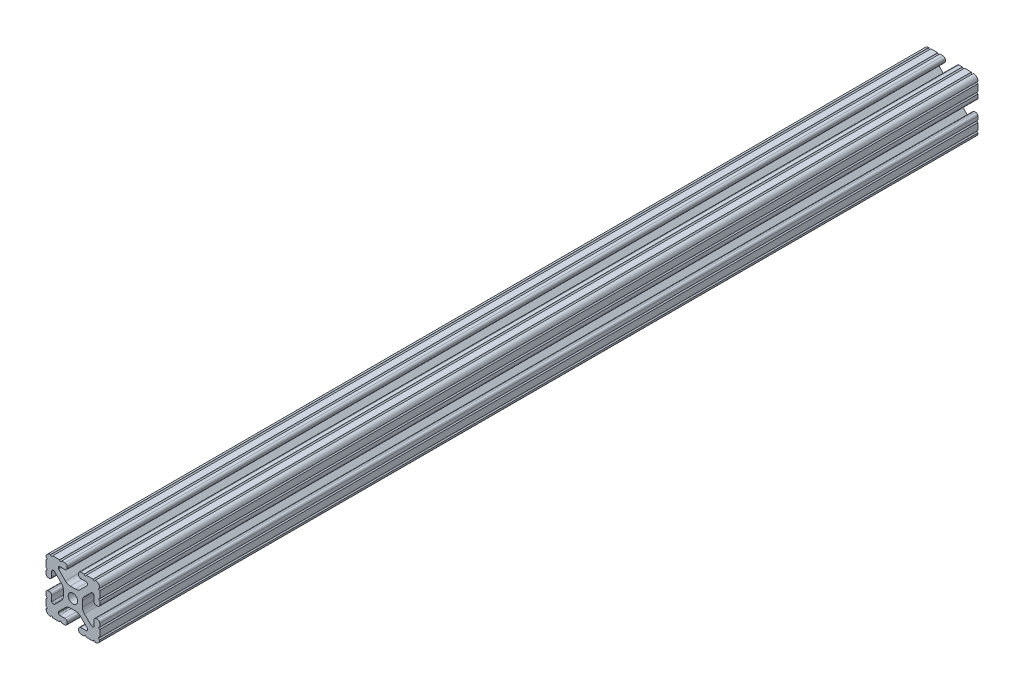
SolidWorks part; units mm, degrees
material "6105-T5 Aluminum"
ref_plane "Front Plane" through (0, 0, 0) normal (0, 0, 1) x (1, 0, 0)
ref_plane "Top Plane" through (0, 0, 0) normal (0, 1, 0) x (1, 0, 0)
ref_plane "Right Plane" through (0, 0, 0) normal (1, 0, 0) x (0, 0, -1)
sketch "Sketch1" plane through (0, 0, 0) normal (0, 0, 1) x (1, 0, 0)
  line L0 (-14.097, 10.287) -> (-13.5289, 10.287)
  line L1 (-12.9003, 10.0266) -> (-8.1292, 5.2555)
  line L2 (-6.738, 1.8969) -> (-6.738, -1.8969)
  line L3 (-8.1292, -5.2555) -> (-12.9003, -10.0266)
  line L4 (-13.5289, -10.287) -> (-14.097, -10.287)
  line L5 (-14.986, -9.398) -> (-14.986, -5.6388)
  line L6 (-16.5608, -4.064) -> (-17.4752, -4.064)
  line L7 (-19.05, -5.6388) -> (-19.05, -7.9756)
  line L8 (-19.05, -9.4996) -> (-19.05, -14.3256)
  line L9 (-19.05, -15.8496) -> (-19.05, -15.875)
  line L10 (-15.875, -19.05) -> (-15.8496, -19.05)
  line L11 (-14.3256, -19.05) -> (-9.4996, -19.05)
  line L12 (-7.9756, -19.05) -> (-5.6388, -19.05)
  line L13 (-4.064, -17.4752) -> (-4.064, -16.5608)
  line L14 (-5.6388, -14.986) -> (-9.398, -14.986)
  line L15 (-10.287, -14.097) -> (-10.287, -13.5289)
  line L16 (-10.0266, -12.9003) -> (-5.2555, -8.1292)
  line L17 (-1.8969, -6.738) -> (1.8969, -6.738)
  line L18 (5.2555, -8.1292) -> (10.0266, -12.9003)
  line L19 (10.287, -13.5289) -> (10.287, -14.097)
  line L20 (9.398, -14.986) -> (5.6388, -14.986)
  line L21 (4.064, -16.5608) -> (4.064, -17.4752)
  line L22 (5.6388, -19.05) -> (7.9756, -19.05)
  line L23 (9.4996, -19.05) -> (14.3256, -19.05)
  line L24 (15.8496, -19.05) -> (15.875, -19.05)
  line L25 (19.05, -15.875) -> (19.05, -15.8496)
  line L26 (19.05, -14.3256) -> (19.05, -9.4996)
  line L27 (19.05, -7.9756) -> (19.05, -5.6388)
  line L28 (17.4752, -4.064) -> (16.5608, -4.064)
  line L29 (14.986, -5.6388) -> (14.986, -9.398)
  line L30 (14.097, -10.287) -> (13.5289, -10.287)
  line L31 (12.9003, -10.0266) -> (8.1292, -5.2555)
  line L32 (6.738, -1.8969) -> (6.738, 1.8969)
  line L33 (8.1292, 5.2555) -> (12.9003, 10.0266)
  line L34 (13.5289, 10.287) -> (14.097, 10.287)
  line L35 (14.986, 9.398) -> (14.986, 5.6388)
  line L36 (16.5608, 4.064) -> (17.4752, 4.064)
  line L37 (19.05, 5.6388) -> (19.05, 7.9756)
  line L38 (19.05, 9.4996) -> (19.05, 14.3256)
  line L39 (19.05, 15.8496) -> (19.05, 15.875)
  line L40 (15.875, 19.05) -> (15.8496, 19.05)
  line L41 (14.3256, 19.05) -> (9.4996, 19.05)
  line L42 (7.9756, 19.05) -> (5.6388, 19.05)
  line L43 (4.064, 17.4752) -> (4.064, 16.5608)
  line L44 (5.6388, 14.986) -> (9.398, 14.986)
  line L45 (10.287, 14.097) -> (10.287, 13.5289)
  line L46 (10.0266, 12.9003) -> (5.2555, 8.1292)
  line L47 (1.8969, 6.738) -> (-1.8969, 6.738)
  line L48 (-5.2555, 8.1292) -> (-10.0266, 12.9003)
  line L49 (-10.287, 13.5289) -> (-10.287, 14.097)
  line L50 (-9.398, 14.986) -> (-5.6388, 14.986)
  line L51 (-4.064, 16.5608) -> (-4.064, 17.4752)
  line L52 (-5.6388, 19.05) -> (-7.9756, 19.05)
  line L53 (-9.4996, 19.05) -> (-14.3256, 19.05)
  line L54 (-15.8496, 19.05) -> (-15.875, 19.05)
  line L55 (-19.05, 15.875) -> (-19.05, 15.8496)
  line L56 (-19.05, 14.3256) -> (-19.05, 9.4996)
  line L57 (-19.05, 7.9756) -> (-19.05, 5.6388)
  line L58 (-17.4752, 4.064) -> (-16.5608, 4.064)
  line L59 (-14.986, 5.6388) -> (-14.986, 9.398)
  circle A0 centre (0, 0) radius 3.3274
  arc A1 (-14.097, 10.287) -> (-14.986, 9.398) centre (-14.097, 9.398) ccw
  arc A2 (-12.9003, 10.0266) -> (-13.5289, 10.287) centre (-13.5289, 9.398) ccw
  arc A3 (-6.738, 1.8969) -> (-8.1292, 5.2555) centre (-11.4878, 1.8969) ccw
  arc A4 (-8.1292, -5.2555) -> (-6.738, -1.8969) centre (-11.4878, -1.8969) ccw
  arc A5 (-13.5289, -10.287) -> (-12.9003, -10.0266) centre (-13.5289, -9.398) ccw
  arc A6 (-14.986, -9.398) -> (-14.097, -10.287) centre (-14.097, -9.398) ccw
  arc A7 (-14.986, -5.6388) -> (-16.5608, -4.064) centre (-16.5608, -5.6388) ccw
  arc A8 (-17.4752, -4.064) -> (-19.05, -5.6388) centre (-17.4752, -5.6388) ccw
  arc A9 (-19.05, -9.4996) -> (-19.05, -7.9756) centre (-19.05, -8.7376) ccw
  arc A10 (-19.05, -15.8496) -> (-19.05, -14.3256) centre (-19.05, -15.0876) ccw
  arc A11 (-19.05, -15.875) -> (-15.875, -19.05) centre (-15.875, -15.875) ccw
  arc A12 (-14.3256, -19.05) -> (-15.8496, -19.05) centre (-15.0876, -19.05) ccw
  arc A13 (-7.9756, -19.05) -> (-9.4996, -19.05) centre (-8.7376, -19.05) ccw
  arc A14 (-5.6388, -19.05) -> (-4.064, -17.4752) centre (-5.6388, -17.4752) ccw
  arc A15 (-4.064, -16.5608) -> (-5.6388, -14.986) centre (-5.6388, -16.5608) ccw
  arc A16 (-10.287, -14.097) -> (-9.398, -14.986) centre (-9.398, -14.097) ccw
  arc A17 (-10.0266, -12.9003) -> (-10.287, -13.5289) centre (-9.398, -13.5289) ccw
  arc A18 (-1.8969, -6.738) -> (-5.2555, -8.1292) centre (-1.8969, -11.4878) ccw
  arc A19 (5.2555, -8.1292) -> (1.8969, -6.738) centre (1.8969, -11.4878) ccw
  arc A20 (10.287, -13.5289) -> (10.0266, -12.9003) centre (9.398, -13.5289) ccw
  arc A21 (9.398, -14.986) -> (10.287, -14.097) centre (9.398, -14.097) ccw
  arc A22 (5.6388, -14.986) -> (4.064, -16.5608) centre (5.6388, -16.5608) ccw
  arc A23 (4.064, -17.4752) -> (5.6388, -19.05) centre (5.6388, -17.4752) ccw
  arc A24 (9.4996, -19.05) -> (7.9756, -19.05) centre (8.7376, -19.05) ccw
  arc A25 (15.8496, -19.05) -> (14.3256, -19.05) centre (15.0876, -19.05) ccw
  arc A26 (15.875, -19.05) -> (19.05, -15.875) centre (15.875, -15.875) ccw
  arc A27 (19.05, -14.3256) -> (19.05, -15.8496) centre (19.05, -15.0876) ccw
  arc A28 (19.05, -7.9756) -> (19.05, -9.4996) centre (19.05, -8.7376) ccw
  arc A29 (19.05, -5.6388) -> (17.4752, -4.064) centre (17.4752, -5.6388) ccw
  arc A30 (16.5608, -4.064) -> (14.986, -5.6388) centre (16.5608, -5.6388) ccw
  arc A31 (14.097, -10.287) -> (14.986, -9.398) centre (14.097, -9.398) ccw
  arc A32 (12.9003, -10.0266) -> (13.5289, -10.287) centre (13.5289, -9.398) ccw
  arc A33 (6.738, -1.8969) -> (8.1292, -5.2555) centre (11.4878, -1.8969) ccw
  arc A34 (8.1292, 5.2555) -> (6.738, 1.8969) centre (11.4878, 1.8969) ccw
  arc A35 (13.5289, 10.287) -> (12.9003, 10.0266) centre (13.5289, 9.398) ccw
  arc A36 (14.986, 9.398) -> (14.097, 10.287) centre (14.097, 9.398) ccw
  arc A37 (14.986, 5.6388) -> (16.5608, 4.064) centre (16.5608, 5.6388) ccw
  arc A38 (17.4752, 4.064) -> (19.05, 5.6388) centre (17.4752, 5.6388) ccw
  arc A39 (19.05, 9.4996) -> (19.05, 7.9756) centre (19.05, 8.7376) ccw
  arc A40 (19.05, 15.8496) -> (19.05, 14.3256) centre (19.05, 15.0876) ccw
  arc A41 (19.05, 15.875) -> (15.875, 19.05) centre (15.875, 15.875) ccw
  arc A42 (14.3256, 19.05) -> (15.8496, 19.05) centre (15.0876, 19.05) ccw
  arc A43 (7.9756, 19.05) -> (9.4996, 19.05) centre (8.7376, 19.05) ccw
  arc A44 (5.6388, 19.05) -> (4.064, 17.4752) centre (5.6388, 17.4752) ccw
  arc A45 (4.064, 16.5608) -> (5.6388, 14.986) centre (5.6388, 16.5608) ccw
  arc A46 (10.287, 14.097) -> (9.398, 14.986) centre (9.398, 14.097) ccw
  arc A47 (10.0266, 12.9003) -> (10.287, 13.5289) centre (9.398, 13.5289) ccw
  arc A48 (1.8969, 6.738) -> (5.2555, 8.1292) centre (1.8969, 11.4878) ccw
  arc A49 (-5.2555, 8.1292) -> (-1.8969, 6.738) centre (-1.8969, 11.4878) ccw
  arc A50 (-10.287, 13.5289) -> (-10.0266, 12.9003) centre (-9.398, 13.5289) ccw
  arc A51 (-9.398, 14.986) -> (-10.287, 14.097) centre (-9.398, 14.097) ccw
  arc A52 (-5.6388, 14.986) -> (-4.064, 16.5608) centre (-5.6388, 16.5608) ccw
  arc A53 (-4.064, 17.4752) -> (-5.6388, 19.05) centre (-5.6388, 17.4752) ccw
  arc A54 (-9.4996, 19.05) -> (-7.9756, 19.05) centre (-8.7376, 19.05) ccw
  arc A55 (-15.8496, 19.05) -> (-14.3256, 19.05) centre (-15.0876, 19.05) ccw
  arc A56 (-15.875, 19.05) -> (-19.05, 15.875) centre (-15.875, 15.875) ccw
  arc A57 (-19.05, 14.3256) -> (-19.05, 15.8496) centre (-19.05, 15.0876) ccw
  arc A58 (-19.05, 7.9756) -> (-19.05, 9.4996) centre (-19.05, 8.7376) ccw
  arc A59 (-19.05, 5.6388) -> (-17.4752, 4.064) centre (-17.4752, 5.6388) ccw
  arc A60 (-16.5608, 4.064) -> (-14.986, 5.6388) centre (-16.5608, 5.6388) ccw
extrude "Boss-Extrude1" add sketch "Sketch1" along normal blind 622.3
hole_wizard "#38 (0.25) Diameter Hole1" positions "3DSketch1" profile "Sketch2" hole size "#38" standard "ANSI Inch"
sketch3d "3DSketch1"
  line L0 (1.8969, 6.738, 622.3) -> (-1.8969, 6.738, 622.3) construction
  line L1 (1.8969, 6.738, 0) -> (-1.8969, 6.738, 0) construction
  point P0 (0, 6.738, 438.15)
  point P2 (0, 6.738, 184.15)
  point P5 (0, 0, 0)
  point P14 (0, 0, 0)
  point P15 (0, 0, 0)
  dimension "D1" = 184.15
  dimension "D2" = 184.15
  dimension "D3" = 19.05
sketch "Sketch2" plane through (0, 6.738, 438.15) normal (1, 0, 0) x (0, 0, 1)
  line L0 (0, 0) -> (0, 25.788)
  line L1 (0, 25.788) -> (3.175, 25.788)
  line L2 (3.175, 25.788) -> (3.175, 0)
  line L5 (3.175, 0) -> (0, 0)
  line L11 (0, -6.35) -> (0, 107.95) construction
  dimension "Thru Hole Dia." = 6.35
  dimension "Thru Hole Depth" = 25.788
